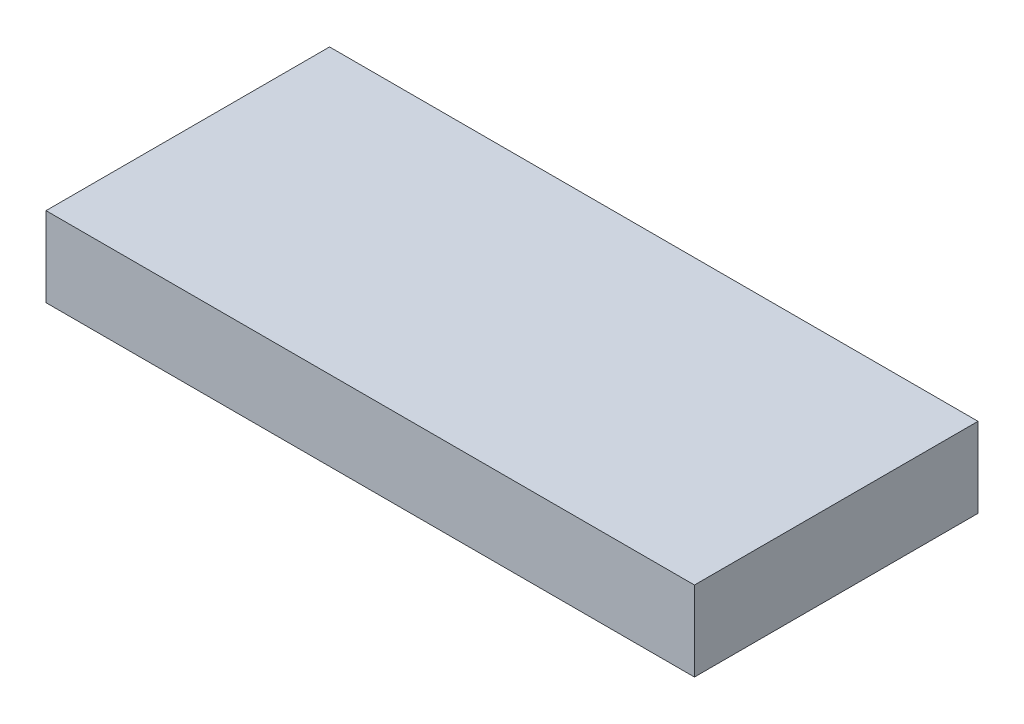
SolidWorks part; units mm, degrees
ref_plane "Plan de face" through (0, 0, 0) normal (0, 0, 1) x (1, 0, 0)
ref_plane "Plan de dessus" through (0, 0, 0) normal (0, 1, 0) x (1, 0, 0)
ref_plane "Plan de droite" through (0, 0, 0) normal (1, 0, 0) x (0, 0, -1)
sketch "Esquisse1" plane through (0, 0, 0) normal (0, 1, 0) x (1, 0, 0)
  line L1 (0, 0) -> (406.6, 0)
  line L2 (0, 0) -> (0, 177.8)
  line L3 (0, 177.8) -> (406.6, 177.8)
  line L4 (406.6, 0) -> (406.6, 177.8)
  dimension "D1" = 406.6
  dimension "D2" = 177.8
extrude "Boss.-Extru.1" add sketch "Esquisse1" along normal blind 50
sketch "Esquisse2" plane through (0, 50, 0) normal (0, 1, 0) x (1, 0, 0)
  line L0 (0, 177.8) -> (0, 0) construction
  line L1 (406.6, 177.8) -> (0, 177.8) construction
  circle A0 centre (134.1, 115.6) radius 21.7913
  dimension "D1" = 134.1
  dimension "D2" = 62.2
